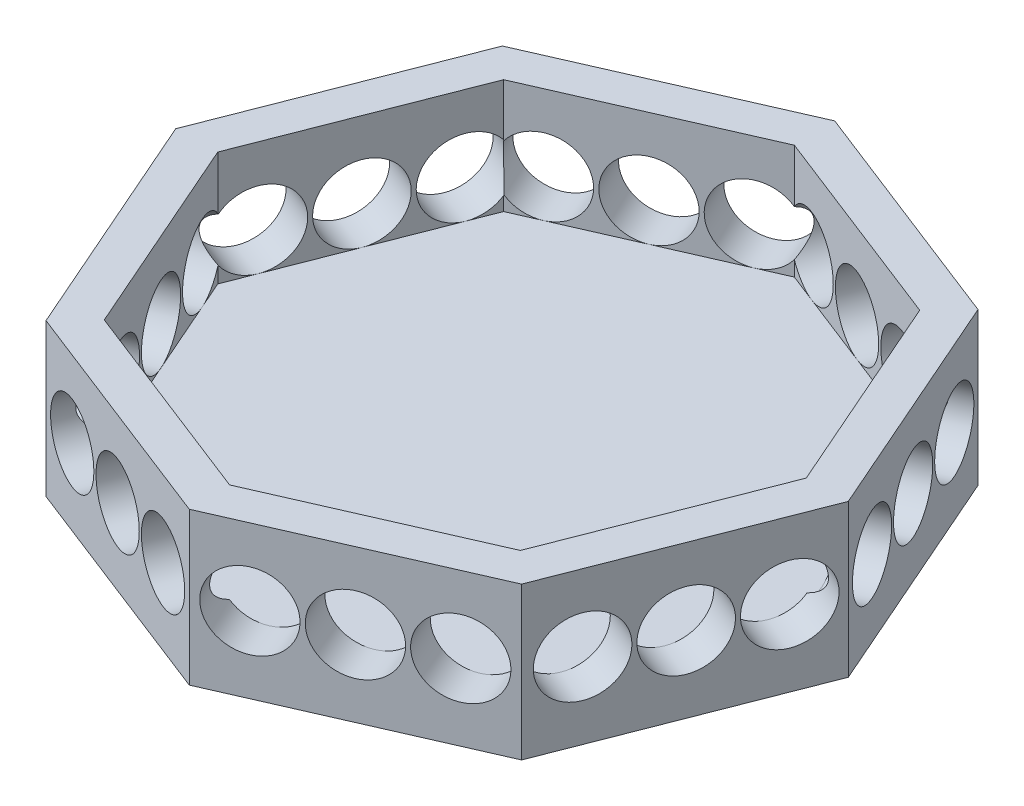
SolidWorks part; units mm, degrees
ref_plane "Front Plane" through (0, 0, 0) normal (0, 0, 1) x (1, 0, 0)
ref_plane "Top Plane" through (0, 0, 0) normal (0, 1, 0) x (1, 0, 0)
ref_plane "Right Plane" through (0, 0, 0) normal (1, 0, 0) x (0, 0, -1)
sketch "Sketch1" plane through (0, 0, 0) normal (0, 1, 0) x (1, 0, 0)
  line L7 (198.259, -190.2647) -> (274.7277, 5.6528)
  line L8 (274.7277, 5.6528) -> (190.2647, 198.259)
  line L9 (190.2647, 198.259) -> (-5.6528, 274.7277)
  line L10 (-5.6528, 274.7277) -> (-198.259, 190.2647)
  line L11 (-198.259, 190.2647) -> (-274.7277, -5.6528)
  line L12 (-274.7277, -5.6528) -> (-190.2647, -198.259)
  line L13 (-190.2647, -198.259) -> (5.6528, -274.7277)
  line L14 (5.6528, -274.7277) -> (198.259, -190.2647)
  circle A0 centre (0, 0) radius 253.869 construction
  dimension "D1" = 210.312
extrude "Boss-Extrude1" add sketch "Sketch1" along normal blind 127
shell "Shell2" thickness 31.75
sketch "Sketch2" plane through (-92.3059, 0, 236.4934) normal (-0.3636, 0, 0.9316) x (0.9316, 0, 0.3636)
  line L1 (-105.156, 127) -> (-105.156, 0) construction
  line L2 (-105.156, 0) -> (105.156, 0) construction
  circle A0 centre (-66.675, 63.5) radius 31.75
  circle A1 centre (0, 63.5) radius 31.75
  circle A2 centre (66.675, 63.5) radius 31.75
  dimension "D1" = 63.5
  dimension "D2" = 105.156
  dimension "D3" = 66.675
  dimension "D4" = 66.675
  dimension "D5" = 63.5
extrude "Cut-Extrude1" cut sketch "Sketch2" against normal through all
sketch "Sketch3" plane through (101.9559, 0, 232.4962) normal (0.4016, 0, 0.9158) x (0.9158, 0, -0.4016)
  line L0 (-105.156, 0) -> (105.156, 0) construction
  circle A0 centre (-66.802, 63.5) radius 31.75
  circle A1 centre (0, 63.5) radius 31.75
  circle A2 centre (66.675, 63.5) radius 31.75
  dimension "D1" = 63.5
  dimension "D2" = 66.802
  dimension "D3" = 66.675
  dimension "D4" = 63.5
  dimension "D5" = 63.5
  dimension "D6" = 63.5
extrude "Cut-Extrude2" cut sketch "Sketch3" against normal through all
sketch "Sketch4" plane through (236.4934, 0, 92.3059) normal (0.9316, 0, 0.3636) x (0.3636, 0, -0.9316)
  line L0 (-105.156, 0) -> (105.156, 0) construction
  circle A0 centre (-65.8694, 63.5) radius 31.75
  circle A1 centre (0.8056, 63.5) radius 31.75
  circle A2 centre (67.4806, 63.5) radius 31.75
  dimension "D1" = 63.5
  dimension "D2" = 66.675
  dimension "D3" = 66.675
  dimension "D4" = 63.5
extrude "Cut-Extrude3" cut sketch "Sketch4" against normal through all
sketch "Sketch5" plane through (232.4962, 0, -101.9559) normal (0.9158, 0, -0.4016) x (-0.4016, 0, -0.9158)
  line L0 (-105.156, 0) -> (105.156, 0) construction
  circle A0 centre (-66.675, 63.5) radius 31.75
  circle A1 centre (0, 63.5) radius 31.75
  circle A2 centre (66.675, 63.5) radius 31.75
  dimension "D1" = 63.5
  dimension "D2" = 63.5
  dimension "D3" = 66.675
  dimension "D4" = 66.675
extrude "Cut-Extrude4" cut sketch "Sketch5" against normal through all and the other way through all
